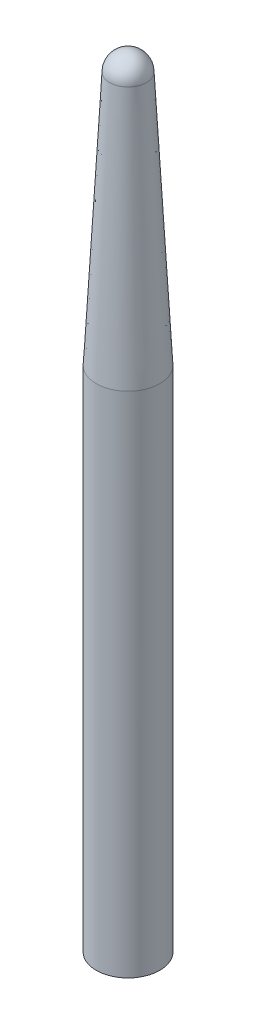
SolidWorks part; units mm, degrees
material "Rubber"
ref_plane "Front Plane" through (0, 0, 0) normal (0, 0, 1) x (1, 0, 0)
ref_plane "Top Plane" through (0, 0, 0) normal (0, 1, 0) x (1, 0, 0)
ref_plane "Right Plane" through (0, 0, 0) normal (1, 0, 0) x (0, 0, -1)
sketch "Sketch1" plane through (0, 0, 0) normal (0, 1, 0) x (1, 0, 0)
  circle A0 centre (0, 0) radius 4.7625
  dimension "D1" = 9.525
extrude "Boss-Extrude1" add sketch "Sketch1" along normal blind 76.2
sketch "Sketch2" plane through (0, 76.2, 0) normal (0, 1, 0) x (1, 0, 0)
  circle A0 centre (0, 0) radius 4.7625
  dimension "D1" = 9.525
extrude "Boss-Extrude2" add sketch "Sketch2" along normal blind 38.1 draft 3
sketch "Sketch3" plane through (0, 114.3, 0) normal (0, 1, 0) x (1, 0, 0)
  line L0 (0, 2.7658) -> (0, -2.7658)
  circle A0 centre (0, 0) radius 2.7658 construction
  arc A1 (0, 2.7658) -> (0, -2.7658) centre (0, 0) cw
revolve "Revolve1" add sketch "Sketch3" angle 360 about L0
hole_wizard "1/4-28 Tapped Hole1" positions "Sketch5" profile "Sketch4" tap size "1/4-28" standard "Ansi Inch"
sketch "Sketch5" plane through (0, 0, 0) normal (0, -1, 0) x (1, 0, 0)
  point P0 (0, 0)
sketch "Sketch4" plane through (0, 0, 0) normal (1, 0, 0) x (0, 0, -1)
  line L0 (0, 0) -> (0, 9.4994)
  line L1 (0, 9.4994) -> (2.7051, 7.874)
  line L2 (2.7051, 7.874) -> (2.7051, 0)
  line L5 (2.7051, 0) -> (0, 0)
  line L10 (0, 9.4994) -> (-2.7051, 7.874) construction
  line L11 (0, -6.35) -> (0, 107.95) construction
  dimension "Tap Drill Dia." = 5.4102
  dimension "Tap Drill Depth" = 7.874
  dimension "Drill Angle" = 118
cosmetic thread "Hole Thread1" parameters "D1"=7.874, "D2"=6.35
